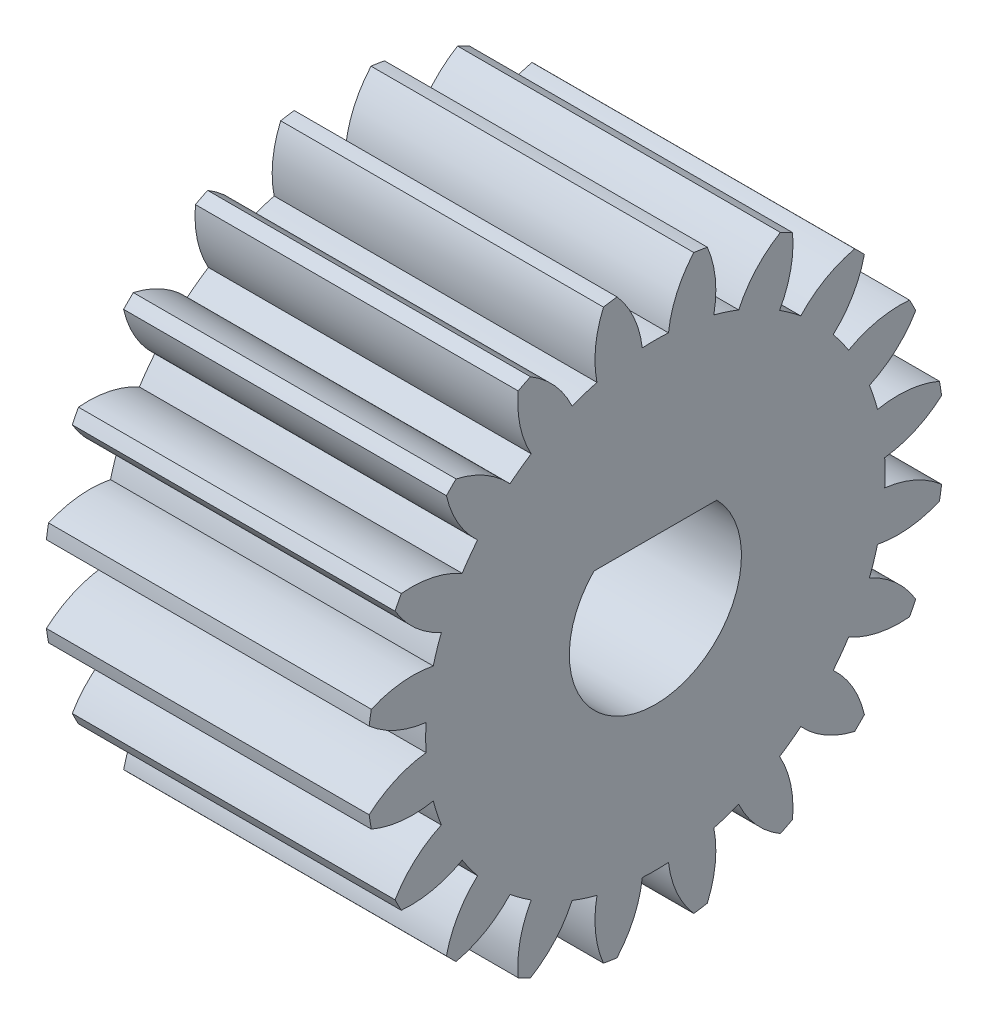
SolidWorks part; units mm, degrees
ref_plane "Plane1" through (0, 0, 0) normal (0, 0, 1) x (1, 0, 0)
ref_plane "Plane2" through (0, 0, 0) normal (0, 1, 0) x (1, 0, 0)
ref_plane "Plane3" through (0, 0, 0) normal (1, 0, 0) x (0, 0, -1)
sketch "HoldingSke" plane through (0, 0, 0) normal (0, 1, 0) x (1, 0, 0)
  line L0 (0, 0) -> (0.7702, -0.2803)
  line L1 (-15, 0) -> (100, 0) construction
  line L2 (0, 0) -> (-2.1039, 2.3779)
  line L3 (0, 0) -> (-11.863, 4.5341)
  line L4 (0, 0) -> (8.1152, 2.9537)
  line L5 (0, 0) -> (-46.8476, -17.4728)
  line L6 (0, 0) -> (-12.4344, -8.3896)
  line L7 (-2.1039, 2.3779) -> (8.6586, 51.2059)
  line L8 (-76.2, 54.61) -> (-74.8, 54.61)
  line L9 (-71.009, 38.7566) -> (-53.1078, 45.2721)
  line L10 (-76.2, 71.12) -> (104.1128, 71.12)
  line L11 (0, 0) -> (-15, 0)
  line L12 (-76.2, 101.6) -> (-76.155, 101.6)
  line L13 (24.9733, 27.94) -> (52.9518, 28.4284)
  line L14 (24.9733, 27.94) -> (24.9743, 27.94)
  line L15 (24.9733, 27.94) -> (100.4006, 29.5858)
  line L16 (-63.627, -1.22) -> (-12.827, -1.22)
  circle A0 centre (0, 0) radius 4
  circle A1 centre (0, 0) radius 10.674
  circle A2 centre (0, 0) radius 37.5
  circle A3 centre (0, 0) radius 4
  dimension "MHD" = 21.348
  dimension "Hub_dia" = 75
  dimension "Bore" = 8
  dimension "MBD" = 8
  dimension "Num_teeth" = 20
  dimension "Pitch" = 0.8197
  dimension "Overall_len" = 50
  dimension "Show_teeth" = 20
  dimension "Thickness" = 15
  dimension "OAL" = 50.0001
  dimension "T_dim" = 1.4
  dimension "Ap" = 20
  dimension "H" = 19.05
  dimension "Pitch_radius" = 180.3128
  dimension "Width" = 15
  dimension "Backlash" = 0.045
  dimension "Addendum_fac" = 1
  dimension "Dedendum_fac" = 1.25
  dimension "Clearance_fac" = 0.25
  dimension "Dedendum_add" = 0.001
  dimension "Module" = 1.22
sketch "BasProSke" plane through (0, 0, 0) normal (0, 1, 0) x (1, 0, 0)
  line L0 (-10, 0) -> (60, 0) construction
  line L1 (0, 0) -> (0, 13.42)
  line L2 (0, 0) -> (15, 0)
  line L3 (15, 0) -> (15, 13.42)
  line L4 (15, 13.42) -> (0, 13.42)
  dimension "Thickness" = 15
  dimension "Diameter" = 26.84
revolve "Base-Revolve" add sketch "BasProSke" angle 360 about L0
sketch "TooCutSke" plane through (0, 0, 0) normal (1, 0, 0) x (0, 0, -1)
  line L1 (0, 0) -> (0, 107) construction
  line L2 (0, 0) -> (-1.0359, 12.1559) construction
  line L3 (0, 0) -> (-3.8071, 24.037) construction
  line L4 (-1.0359, 12.1559) -> (-1.9035, 12.0185) construction
  arc A0 (0.6078, 10.6567) -> (-0.6078, 10.6567) centre (0, 0) ccw
  arc A1 (1.8049, 13.3237) -> (-1.8049, 13.3237) centre (0, 0) ccw
  circle A2 centre (0, 0) radius 12.2 construction
  circle A3 centre (0, 0) radius 11.4642 construction
  arc A4 (-0.6078, 10.6567) -> (-1.8049, 13.3237) centre (-5.4541, 10.0837) ccw
  arc A5 (1.8049, 13.3237) -> (0.6078, 10.6567) centre (5.4541, 10.0837) ccw
  dimension "Root_dia" = 21.348
  dimension "Overcut_dia" = 26.8908
  dimension "Pitch_dia" = 24.4
  dimension "Base_dia" = 22.9285
  dimension "Flank_rad" = 4.88
  dimension "Half_ang" = 9
  dimension "Half_CT" = 0.8785
extrude "ToothCut" cut sketch "TooCutSke" along normal through all
fillet "Breaks" [suppressed] radius 0.0244
fillet "RootFillets" [suppressed] radius 0.306
pattern_circular "TeethCuts" count 20 every 18 about axis through (-10, 0, 0) along (1, 0, 0) of "ToothCut", "RootFillets", "Breaks"
sketch "HubNeaOneSke" plane through (0, 0, 0) normal (-1, 0, 0) x (0, 0, 1)
  circle A0 centre (0, 0) radius 10.674
  dimension "Diameter" = 21.348
extrude "HubNearOne" [suppressed] add sketch "HubNeaOneSke" along normal blind 35.0001
sketch "HubNeaBotSke" plane through (0, 0, 0) normal (-1, 0, 0) x (0, 0, 1)
  circle A0 centre (0, 0) radius 10.674
  dimension "Diameter" = 21.348
extrude "HubNearBoth" [suppressed] add sketch "HubNeaBotSke" along normal blind 17.5
ref_plane "FarPln" through (15, 0, 0) normal (1, 0, 0) x (0, 0, -1)
sketch "HubFarSke" plane through (15, 0, 0) normal (1, 0, 0) x (0, 0, -1)
  circle A0 centre (0, 0) radius 10.674
  dimension "Diameter" = 21.348
extrude "HubFar" [suppressed] add sketch "HubFarSke" along normal blind 17.5
sketch "BorSke" plane through (0, 0, 0) normal (1, 0, 0) x (0, 0, -1)
  circle A0 centre (0, 0) radius 4
  dimension "Diameter" = 8
extrude "Bore" cut sketch "BorSke" along normal mid plane 100.0001
sketch "KeySke" plane through (0, 0, 0) normal (1, 0, 0) x (0, 0, -1)
  line L0 (-1.5, 0) -> (-1.5, 5.4)
  line L1 (-1.5, 5.4) -> (1.5, 5.4)
  line L2 (1.5, 5.4) -> (1.5, 0)
  line L3 (0, 0) -> (0, 34) construction
  line L4 (-1.5, 0) -> (1.5, 0)
  dimension "Offset" = 5.4
  dimension "Width" = 3
extrude "Keyway" [suppressed] cut sketch "KeySke" along normal mid plane 100.0001
pattern_circular "Keyway2" [suppressed] count 2 every 90 about axis through (-10, 0, 0) along (1, 0, 0)
sketch "Sketch1" plane through (0, 0, 0) normal (-1, 0, 0) x (0, 0, 1)
  line L0 (-2.8566, 2.8) -> (2.8566, 2.8)
  line L1 (0, 0) -> (0, 2.8) construction
  line L2 (0, 2.8) -> (0, 4) construction
  circle A0 centre (0, 0) radius 4 construction
  arc A1 (-2.8566, 2.8) -> (2.8566, 2.8) centre (0, 0) cw
  dimension "D1" = 8
  dimension "D2" = 1.2
extrude "Boss-Extrude1" add sketch "Sketch1" against normal up to surface (15 mm away) up to face at (15, 0, 4)
sketch "Sketch2" plane through (0, 0, 0) normal (-1, 0, 0) x (0, 0, 1)
  line L0 (0, 0) -> (-7, 0) construction
  line L2 (-7.6, 4) -> (-6.4, 4)
  line L3 (-7.6, 4) -> (-7.6, -4)
  line L4 (-7.6, -4) -> (-6.4, -4)
  line L5 (-6.4, 4) -> (-6.4, -4)
  line L6 (-7.6, 4) -> (-6.4, -4) construction
  line L7 (-7.6, -4) -> (-6.4, 4) construction
  dimension "D1" = 7
  dimension "D2" = 8
  dimension "D3" = 1.2
extrude "Cut-Extrude1" cut sketch "Sketch2" against normal blind 2
equation "' \"Module@HoldingSke\" = 6.35"
equation "' \"Num_teeth@HoldingSke\" = 12"
equation "' \"Ap@HoldingSke\" =  20"
equation "' \"Ap@HoldingSke\" = 20"
equation "' \"Width@HoldingSke\" = 0.5 * 25.4"
equation "' \"Hub_dia@HoldingSke\"= 1 * 25.4"
equation "' \"Hub_dia@HoldingSke\" = 1 * 25.4"
equation "' \"Overall_len@HoldingSke\" = 1.0 * 25.4"
equation "' \"Bore@HoldingSke\" = 0.75 * 25.4"
equation "' \"T_dim@HoldingSke\" = 0.1 * 25.4"
equation "' \"Width@KeySke\" = 0.25 * 25.4"
equation "' \"Show_teeth@HoldingSke\" = 13"
equation "' \"Backlash@HoldingSke\" = 0.009 * 25.4"
equation "' \"Addendum_fac@HoldingSke\" = 1.0"
equation "' \"Dedendum_fac@HoldingSke\" = 1.25"
equation "' \"Dedendum_add@HoldingSke\" = 0.00005 * 25.4"
equation "' \"Clearance_fac@HoldingSke\" = 0.25"
equation "\"Pitch@HoldingSke\" = 1 / \"Module@HoldingSke\""
equation "\"Overcut_dia@TooCutSke\" = (\"Num_teeth@HoldingSke\" + 2 * \"Addendum_fac@HoldingSke\") / \"Pitch@HoldingSke\" + 0.002 * 25.4"
equation "\"Pitch_dia@TooCutSke\" = \"Num_teeth@HoldingSke\" / \"Pitch@HoldingSke\""
equation "\"Base_dia@TooCutSke\" = \"Num_teeth@HoldingSke\" / \"Pitch@HoldingSke\" * cos((\"Ap@HoldingSke\"  * 3.14159265 / 180))"
equation "\"Root_dia@TooCutSke\" = (\"Num_teeth@HoldingSke\" + 2) / \"Pitch@HoldingSke\" - 2 * (\"Addendum_fac@HoldingSke\" + \"Dedendum_fac@HoldingSke\") / \"Pitch@HoldingSke\" - \"Dedendum_add@HoldingSke\" * 2"
equation "\"Half_ang@TooCutSke\" = 180 / \"Num_teeth@HoldingSke\""
equation "\"Half_CT@TooCutSke\" = \"Num_teeth@HoldingSke\" / \"Pitch@HoldingSke\" * sin((3.14159265 / 2 / \"Num_teeth@HoldingSke\")) / 2 - 7 * \"Backlash@HoldingSke\" / 4"
equation "\"Flank_rad@TooCutSke\" = \"Num_teeth@HoldingSke\" / \"Pitch@HoldingSke\" / 5"
equation "\"Radius@RootFillets\" = \"Clearance_fac@HoldingSke\" / \"Pitch@HoldingSke\" + \"Dedendum_add@HoldingSke\""
equation "\"Break_rad@Breaks\" = 0.02 / \"Pitch@HoldingSke\""
equation "\"Thickness@HoldingSke\" = \"Width@HoldingSke\""
equation "\"OAL@HoldingSke\" = \"Thickness@HoldingSke\""
equation "\"MHD@HoldingSke\" = (\"Num_teeth@HoldingSke\" + 2) / \"Pitch@HoldingSke\" - 2 * (\"Addendum_fac@HoldingSke\" + \"Dedendum_fac@HoldingSke\")  / \"Pitch@HoldingSke\" - \"Dedendum_add@HoldingSke\" * 2"
equation "\"MBD@HoldingSke\" = (\"Num_teeth@HoldingSke\" + 2) / \"Pitch@HoldingSke\" - 2 * (\"Addendum_fac@HoldingSke\" + \"Dedendum_fac@HoldingSke\")  / \"Pitch@HoldingSke\" - \"Dedendum_add@HoldingSke\" * 2 - 0.002 * 25.4"
equation "\"MHD@HoldingSke\" = ((sgn( \"MHD@HoldingSke\" - \"Hub_dia@HoldingSke\" )-1)*( \"MHD@HoldingSke\" - \"Hub_dia@HoldingSke\" ))/-2+ \"Hub_dia@HoldingSke\""
equation "\"MBD@HoldingSke\" = ((sgn( \"MBD@HoldingSke\" - \"Bore@HoldingSke\" )-1)*( \"MBD@HoldingSke\" - \"Bore@HoldingSke\" ))/-2+ \"Bore@HoldingSke\""
equation "\"OAL@HoldingSke\" = ((sgn( \"OAL@HoldingSke\" - \"Overall_len@HoldingSke\" )+1)*( \"OAL@HoldingSke\" - \"Overall_len@HoldingSke\" ))/2 + \"Overall_len@HoldingSke\" + 0.000002 * 25.4"
equation "\"Num_teeth@TeethCuts\" = int( \"Show_teeth@HoldingSke\" ) + 1"
equation "\"Num_teeth@TeethCuts\" = ((sgn( \"Num_teeth@TeethCuts\" - \"Num_teeth@HoldingSke\" )-1)*( \"Num_teeth@TeethCuts\" - \"Num_teeth@HoldingSke\" ))/-2+ \"Num_teeth@HoldingSke\""
equation "\"Num_teeth@TeethCuts\" = ((sgn( \"Num_teeth@TeethCuts\" - 2.0)+1)*( \"Num_teeth@TeethCuts\" - 2.0))/2 +2.0"
equation "\"Angle@TeethCuts\" = 360.0 / \"Num_teeth@HoldingSke\""
equation "\"Diameter@BasProSke\" = (\"Num_teeth@HoldingSke\" + 2 * \"Addendum_fac@HoldingSke\") / \"Pitch@HoldingSke\""
equation "\"Thickness@BasProSke\"  = \"Thickness@HoldingSke\""
equation "' \"Fillet_rad@BasProSke\" =  \"Thickness@HoldingSke\" * 0.05"
equation "' \"Fillet_rad@BasProSke\" = \"Thickness@HoldingSke\" * 0.05"
equation "\"MHD@HoldingSke\" = ((sgn( \"MHD@HoldingSke\" - \"Root_dia@TooCutSke\" )-1)*( \"MHD@HoldingSke\" - \"Root_dia@TooCutSke\" ))/-2+ \"Root_dia@TooCutSke\""
equation "\"Diameter@HubNeaOneSke\" = \"MHD@HoldingSke\""
equation "\"Length@HubNearOne\" = \"OAL@HoldingSke\" - \"Thickness@BasProSke\""
equation "\"Diameter@HubNeaBotSke\" = \"MHD@HoldingSke\""
equation "\"Length@HubNearBoth\" = ( \"OAL@HoldingSke\" - \"Thickness@BasProSke\" ) / 2.0"
equation "\"Thickness@FarPln\" = \"Thickness@BasProSke\""
equation "\"Diameter@HubFarSke\" = \"MHD@HoldingSke\""
equation "\"Length@HubFar\" = ( \"OAL@HoldingSke\" - \"Thickness@BasProSke\" ) / 2.0"
equation "\"Diameter@BorSke\" = \"MBD@HoldingSke\""
equation "\"D1@Bore\" = \"OAL@HoldingSke\" * 2.0"
equation "\"D1@Keyway\" = \"OAL@HoldingSke\" * 2.0"
equation "\"Offset@KeySke\" = \"T_dim@HoldingSke\" + \"MBD@HoldingSke\" / 2.0"
